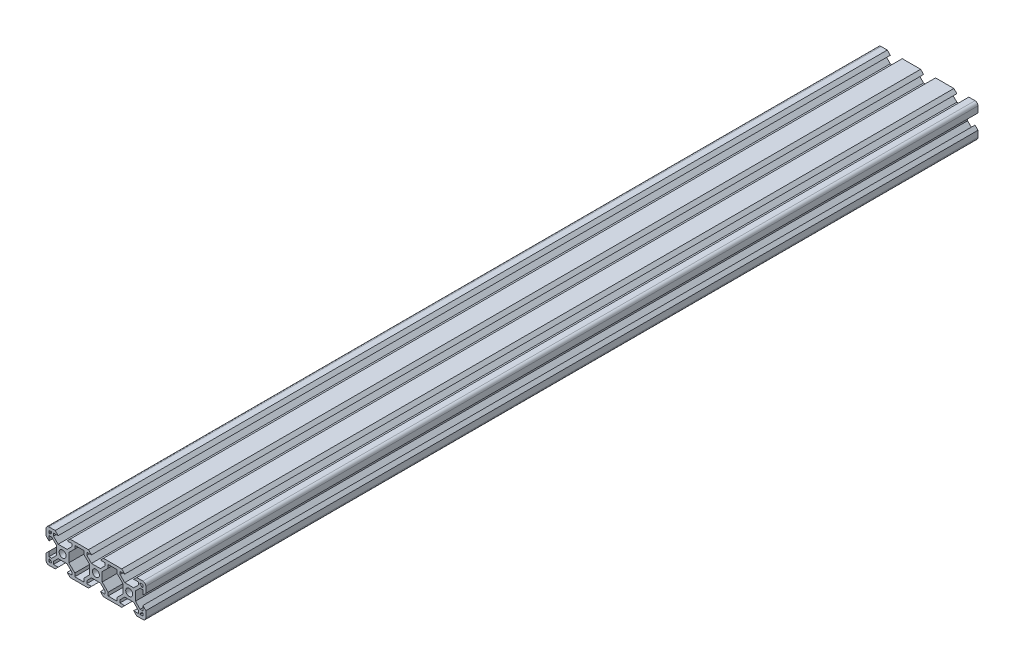
SolidWorks part; units mm, degrees
material "5052-H38, Barre (SS)"
ref_plane "Plan de face" through (0, 0, 0) normal (0, 0, 1) x (1, 0, 0)
ref_plane "Plan de dessus" through (0, 0, 0) normal (0, 1, 0) x (1, 0, 0)
ref_plane "Plan de droite" through (0, 0, 0) normal (1, 0, 0) x (0, 0, -1)
sketch "Esquisse1" plane through (0, 0, 0) normal (0, 0, 1) x (1, 0, 0)
  line L0 (0, 0) -> (-30, 0) construction
  line L1 (0, 0) -> (0, 10) construction
  line L2 (-20, 0) -> (-30, 10) construction
  line L3 (-20, 3.7507) -> (-22.69, 3.7507)
  line L4 (-22.69, 3.7507) -> (-25.4993, 6.56)
  line L5 (-25.4993, 6.56) -> (-25.4993, 8.2)
  line L6 (-25.4993, 8.2) -> (-22.69, 8.2)
  line L7 (-22.69, 8.2) -> (-24.49, 10)
  line L8 (-24.49, 10) -> (-28.2, 10)
  line L9 (-20, 0) -> (-20, 10) construction
  line L10 (-30, 4.49) -> (-30, 8.2)
  line L11 (-28.2, 2.69) -> (-30, 4.49)
  line L12 (-28.2, 5.4993) -> (-28.2, 2.69)
  line L13 (-26.56, 5.4993) -> (-28.2, 5.4993)
  line L14 (-23.7507, 2.69) -> (-26.56, 5.4993)
  line L15 (-23.7507, 0) -> (-23.7507, 2.69)
  line L16 (-28.2, 8.2) -> (-28.2, 6.5693)
  line L17 (-28.2, 6.5693) -> (-27.63, 6.5693)
  line L18 (-27.63, 6.5693) -> (-26.5693, 7.63)
  line L19 (-26.5693, 7.63) -> (-26.5693, 8.2)
  line L20 (-26.5693, 8.2) -> (-28.2, 8.2)
  line L21 (-23.7507, 0) -> (-23.7507, -2.69)
  line L22 (-23.7507, -2.69) -> (-26.56, -5.4993)
  line L23 (-26.56, -5.4993) -> (-28.2, -5.4993)
  line L24 (-28.2, -5.4993) -> (-28.2, -2.69)
  line L25 (-28.2, -2.69) -> (-30, -4.49)
  line L26 (-30, -4.49) -> (-30, -8.2)
  line L27 (-24.49, -10) -> (-28.2, -10)
  line L28 (-22.69, -8.2) -> (-24.49, -10)
  line L29 (-25.4993, -8.2) -> (-22.69, -8.2)
  line L30 (-25.4993, -6.56) -> (-25.4993, -8.2)
  line L31 (-22.69, -3.7507) -> (-25.4993, -6.56)
  line L32 (-20, -3.7507) -> (-22.69, -3.7507)
  line L33 (-26.5693, -7.63) -> (-27.63, -6.5693)
  line L34 (-27.63, -6.5693) -> (-28.2, -6.5693)
  line L35 (-28.2, -6.5693) -> (-28.2, -8.2)
  line L36 (-28.2, -8.2) -> (-26.5693, -8.2)
  line L37 (-26.5693, -8.2) -> (-26.5693, -7.63)
  line L38 (-2.69, -8.2) -> (-4.49, -10)
  line L39 (-2.69, 8.2) -> (-4.49, 10)
  line L40 (-7.3007, -8.2) -> (-7.3007, -6.24)
  line L41 (-7.3007, -6.24) -> (-3.7507, -2.69)
  line L42 (-3.7507, 2.69) -> (-3.7507, -2.69)
  line L43 (-7.3007, 6.24) -> (-3.7507, 2.69)
  line L44 (-7.3007, 8.2) -> (-7.3007, 6.24)
  line L45 (26.5693, 8.2) -> (28.2, 8.2)
  line L46 (26.5693, 7.63) -> (26.5693, 8.2)
  line L47 (27.63, 6.5693) -> (26.5693, 7.63)
  line L48 (28.2, 6.5693) -> (27.63, 6.5693)
  line L49 (28.2, 8.2) -> (28.2, 6.5693)
  line L50 (26.5693, -8.2) -> (26.5693, -7.63)
  line L51 (28.2, -8.2) -> (26.5693, -8.2)
  line L52 (28.2, -6.5693) -> (28.2, -8.2)
  line L53 (27.63, -6.5693) -> (28.2, -6.5693)
  line L54 (26.5693, -7.63) -> (27.63, -6.5693)
  line L55 (7.3007, 8.2) -> (7.3007, 6.24)
  line L56 (7.3007, 8.2) -> (12.6993, 8.2)
  line L57 (12.6993, 8.2) -> (12.6993, 6.24)
  line L58 (12.6993, 6.24) -> (16.2493, 2.69)
  line L59 (16.2493, 2.69) -> (16.2493, -2.69)
  line L60 (12.6993, -6.24) -> (16.2493, -2.69)
  line L61 (12.6993, -8.2) -> (12.6993, -6.24)
  line L62 (7.3007, -8.2) -> (12.6993, -8.2)
  line L63 (7.3007, -8.2) -> (7.3007, -6.24)
  line L64 (7.3007, -6.24) -> (3.7507, -2.69)
  line L65 (3.7507, 2.69) -> (3.7507, -2.69)
  line L66 (7.3007, 6.24) -> (3.7507, 2.69)
  line L67 (2.69, -8.2) -> (4.49, -10)
  line L68 (15.51, -10) -> (4.49, -10)
  line L69 (17.31, -8.2) -> (15.51, -10)
  line L70 (14.5007, -8.2) -> (17.31, -8.2)
  line L71 (14.5007, -6.56) -> (14.5007, -8.2)
  line L72 (17.31, -3.7507) -> (14.5007, -6.56)
  line L73 (20, -3.7507) -> (17.31, -3.7507)
  line L74 (20, -3.7507) -> (22.69, -3.7507)
  line L75 (22.69, -3.7507) -> (25.4993, -6.56)
  line L76 (25.4993, -6.56) -> (25.4993, -8.2)
  line L77 (25.4993, -8.2) -> (22.69, -8.2)
  line L78 (22.69, -8.2) -> (24.49, -10)
  line L79 (24.49, -10) -> (28.2, -10)
  line L80 (30, -4.49) -> (30, -8.2)
  line L81 (28.2, -2.69) -> (30, -4.49)
  line L82 (28.2, -5.4993) -> (28.2, -2.69)
  line L83 (26.56, -5.4993) -> (28.2, -5.4993)
  line L84 (0, 0) -> (-10, 10) construction
  line L85 (-17.31, 3.7507) -> (-14.5007, 6.56)
  line L86 (-14.5007, 6.56) -> (-14.5007, 8.2)
  line L87 (-14.5007, 8.2) -> (-17.31, 8.2)
  line L88 (-17.31, 8.2) -> (-15.51, 10)
  line L89 (-20, 3.7507) -> (-17.31, 3.7507)
  line L90 (-20, -3.7507) -> (-17.31, -3.7507)
  line L91 (-17.31, -3.7507) -> (-14.5007, -6.56)
  line L92 (-14.5007, -6.56) -> (-14.5007, -8.2)
  line L93 (-14.5007, -8.2) -> (-17.31, -8.2)
  line L94 (-17.31, -8.2) -> (-15.51, -10)
  line L95 (-10, 10) -> (-10, 0) construction
  line L96 (-15.51, 10) -> (-4.49, 10)
  line L97 (-15.51, -10) -> (-4.49, -10)
  line L98 (-7.3007, 8.2) -> (-12.6993, 8.2)
  line L99 (-12.6993, 8.2) -> (-12.6993, 6.24)
  line L100 (-12.6993, 6.24) -> (-16.2493, 2.69)
  line L101 (-16.2493, 2.69) -> (-16.2493, -2.69)
  line L102 (-20, 0) -> (-10, 10) construction
  line L103 (-17.31, 3.7507) -> (-16.2493, 2.69) construction
  line L104 (-12.6993, -6.24) -> (-16.2493, -2.69)
  line L105 (-12.6993, -8.2) -> (-12.6993, -6.24)
  line L106 (-7.3007, -8.2) -> (-12.6993, -8.2)
  line L107 (23.7507, -2.69) -> (26.56, -5.4993)
  line L108 (23.7507, 0) -> (23.7507, -2.69)
  line L109 (23.7507, 0) -> (23.7507, 2.69)
  line L110 (23.7507, 2.69) -> (26.56, 5.4993)
  line L111 (26.56, 5.4993) -> (28.2, 5.4993)
  line L112 (28.2, 5.4993) -> (28.2, 2.69)
  line L113 (28.2, 2.69) -> (30, 4.49)
  line L114 (30, 4.49) -> (30, 8.2)
  line L115 (24.49, 10) -> (28.2, 10)
  line L116 (22.69, 8.2) -> (24.49, 10)
  line L117 (25.4993, 8.2) -> (22.69, 8.2)
  line L118 (25.4993, 6.56) -> (25.4993, 8.2)
  line L119 (22.69, 3.7507) -> (25.4993, 6.56)
  line L120 (20, 3.7507) -> (22.69, 3.7507)
  line L121 (20, 3.7507) -> (17.31, 3.7507)
  line L122 (17.31, 3.7507) -> (14.5007, 6.56)
  line L123 (14.5007, 6.56) -> (14.5007, 8.2)
  line L124 (14.5007, 8.2) -> (17.31, 8.2)
  line L125 (17.31, 8.2) -> (15.51, 10)
  line L126 (15.51, 10) -> (4.49, 10)
  line L127 (2.69, 8.2) -> (4.49, 10)
  line L128 (-2.69, 8.2) -> (-5.4993, 8.2)
  line L129 (-5.4993, 8.2) -> (-5.4993, 6.56)
  line L130 (-5.4993, 6.56) -> (-2.69, 3.7507)
  line L131 (-2.69, 3.7507) -> (2.69, 3.7507)
  line L132 (5.4993, 6.56) -> (2.69, 3.7507)
  line L133 (5.4993, 8.2) -> (5.4993, 6.56)
  line L134 (5.4993, 8.2) -> (2.69, 8.2)
  line L135 (2.69, 8.2) -> (5.4993, 8.2)
  line L136 (5.4993, -8.2) -> (2.69, -8.2)
  line L137 (5.4993, -8.2) -> (5.4993, -6.56)
  line L138 (5.4993, -6.56) -> (2.69, -3.7507)
  line L139 (-2.69, -3.7507) -> (2.69, -3.7507)
  line L140 (-5.4993, -6.56) -> (-2.69, -3.7507)
  line L141 (-5.4993, -8.2) -> (-5.4993, -6.56)
  line L142 (-2.69, -8.2) -> (-5.4993, -8.2)
  circle A0 centre (0, 0) radius 2.1
  circle A1 centre (-20, 0) radius 2.1
  arc A2 (-28.2, 10) -> (-30, 8.2) centre (-28.2, 8.2) ccw
  arc A3 (-30, -8.2) -> (-28.2, -10) centre (-28.2, -8.2) ccw
  circle A4 centre (20, 0) radius 2.1
  arc A5 (30, -8.2) -> (28.2, -10) centre (28.2, -8.2) cw
  arc A6 (28.2, 10) -> (30, 8.2) centre (28.2, 8.2) cw
  point P26 (-27.0997, 7.0997)
  point P32 (-10, -10)
  point P55 (-10, -8.2)
  point P61 (-10, 8.2)
  point P106 (-16.7797, 3.2203)
  point P108 (-16.2493, 0)
  point P153 (0, 3.7507)
  point P154 (0, 3.7507)
  dimension "D3" = 4.2
  dimension "D1" = 30
  dimension "D2" = 10
  dimension "D5" = 20
  dimension "D6" = 1.5
  dimension "D7" = 1.64
  dimension "D8" = 1.8
  dimension "D9" = 5.38
  dimension "D10" = 1.07
  dimension "D12" = 45
  dimension "D15" = 1.96
  dimension "D4" = 2
  dimension "D11" = 2
  dimension "D13" = 2
  dimension "D14" = 2
extrude "Boss.-Extru.1" add sketch "Esquisse1" along normal mid plane 500 contours A6 L115 L116 L117 L118 L119 L120 L121 L122 L123 L124 L125 L126 L127 L134 L133 L132 L131 L130 L129 L128 L39 L96 L88 L87 L86 L85 L89 L3 L4 L5 L6 L7 L8 A2 L10 L11 L12 L13 L14 L15 L21 L22 L23 L24 L25 L26 A3 L27 L28 L29
